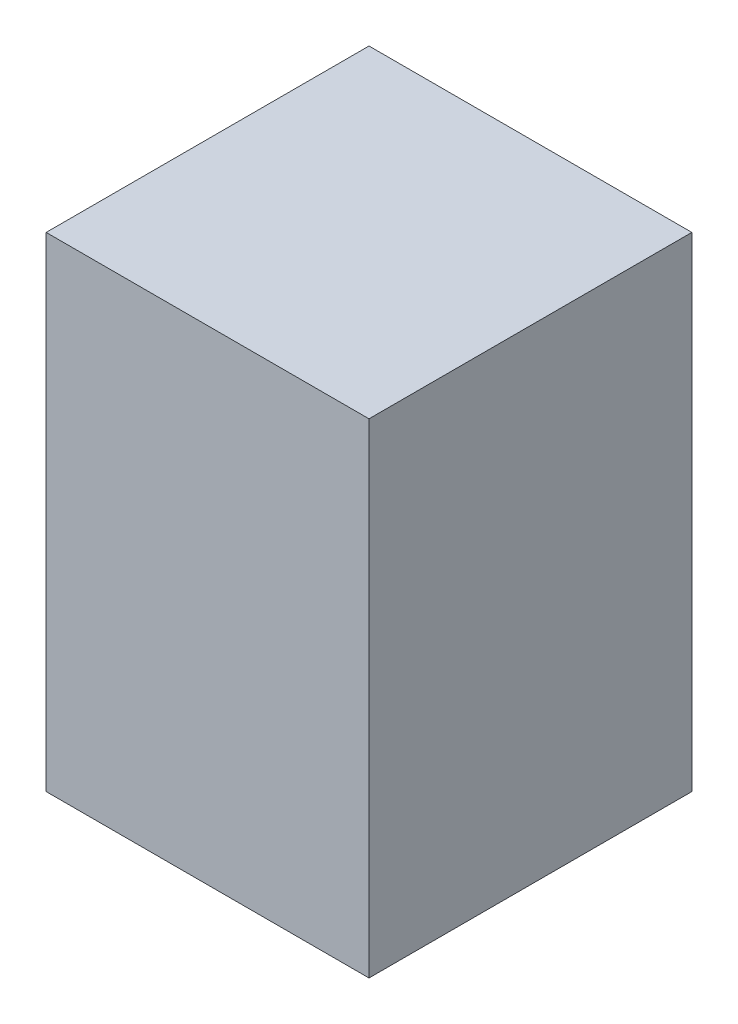
SolidWorks part; units mm, degrees
ref_plane "Front" through (0, 0, 0) normal (0, 0, 1) x (1, 0, 0)
ref_plane "Top" through (0, 0, 0) normal (0, 1, 0) x (1, 0, 0)
ref_plane "Right" through (0, 0, 0) normal (1, 0, 0) x (0, 0, -1)
sketch "Sketch1" plane through (0, 0, 0) normal (0, 0, 1) x (1, 0, 0)
  line L1 (0, 0) -> (-10, 0)
  line L2 (0, 0) -> (0, 15)
  line L3 (0, 15) -> (-10, 15)
  line L4 (-10, 0) -> (-10, 15)
  point P5 (-10, 7.5)
extrude "Boss-Extrude1" add sketch "Sketch1" along normal blind 10
